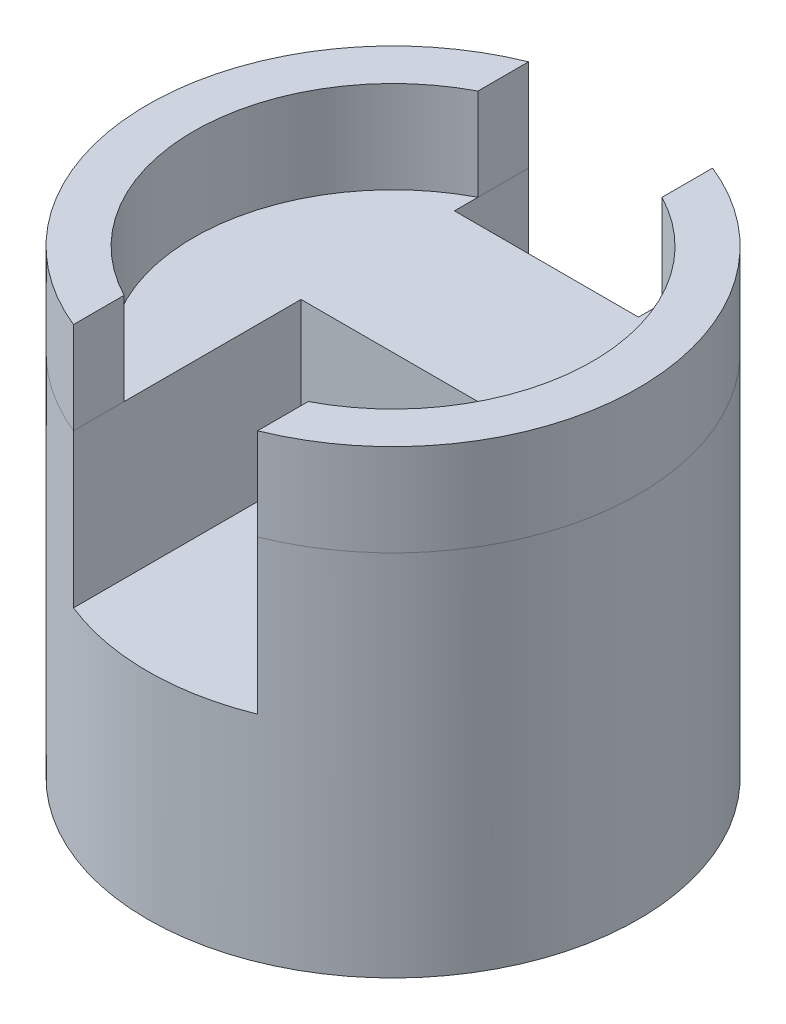
SolidWorks part; units mm, degrees
ref_plane "Front Plane" through (0, 0, 0) normal (0, 0, 1) x (1, 0, 0)
ref_plane "Top Plane" through (0, 0, 0) normal (0, 1, 0) x (1, 0, 0)
ref_plane "Right Plane" through (0, 0, 0) normal (1, 0, 0) x (0, 0, -1)
sketch "Sketch2" plane through (0, 0, 0) normal (0, 1, 0) x (1, 0, 0)
  circle A0 centre (0, 0) radius 101.6
  dimension "D1" = 203.2
extrude "Boss-Extrude1" add sketch "Sketch2" along normal blind 152.4
sketch "Sketch3" plane through (0, 152.4, 0) normal (0, 1, 0) x (1, 0, 0)
  circle A0 centre (0, 0) radius 82.55
  circle A1 centre (0, 0) radius 101.6 construction
  circle A2 centre (0, 0) radius 101.6
  dimension "D1" = 165.1
extrude "Boss-Extrude2" add sketch "Sketch3" along normal blind 38.1 separate body
sketch "Sketch4" plane through (0, 190.5, 0) normal (0, 1, 0) x (1, 0, 0)
  line L1 (-38.1, 0) -> (38.1, 0)
  line L2 (-38.1, 0) -> (-38.1, -101.6)
  line L3 (-38.1, -101.6) -> (38.1, -101.6)
  line L4 (38.1, 0) -> (38.1, -101.6)
  line L13 (0, 0) -> (0, 101.6) construction
  circle A0 centre (0, 0) radius 101.6 construction
  point P4 (0, 0)
  dimension "D1" = 76.2
extrude "Cut-Extrude1" cut sketch "Sketch4" against normal blind 101.6
sketch "Sketch5" plane through (0, 190.5, 0) normal (0, 1, 0) x (1, 0, 0)
  line L0 (38.1, -94.1857) -> (38.1, 0) construction
  line L1 (-38.1, 63.5) -> (38.1, 63.5)
  line L2 (-38.1, 63.5) -> (-38.1, 101.6)
  line L3 (-38.1, 101.6) -> (38.1, 101.6)
  line L4 (38.1, 63.5) -> (38.1, 101.6)
  arc A0 (38.1, -94.1857) -> (-38.1, -94.1857) centre (0, 0) ccw construction
  point P4 (0, 63.5)
  dimension "D1" = 38.1
extrude "Cut-Extrude2" cut sketch "Sketch5" against normal through all
